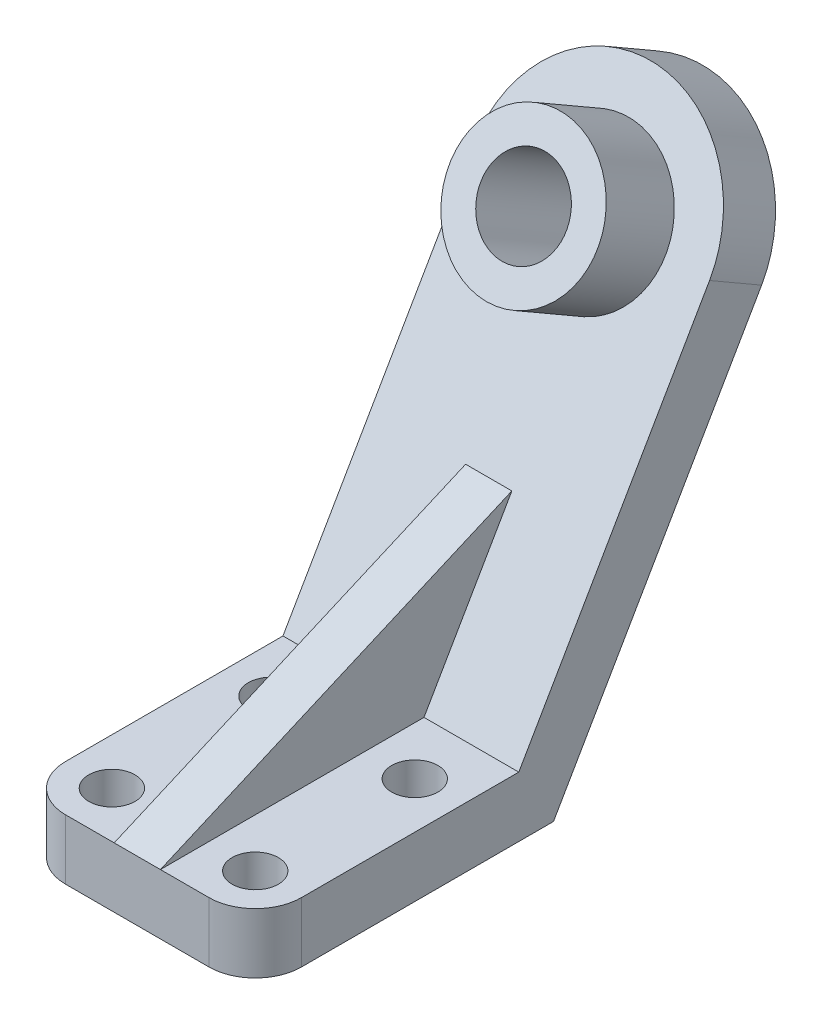
SolidWorks part; units mm, degrees
ref_plane "Front Plane" through (0, 0, 0) normal (0, 0, 1) x (1, 0, 0)
ref_plane "Top Plane" through (0, 0, 0) normal (0, 1, 0) x (1, 0, 0)
ref_plane "Right Plane" through (0, 0, 0) normal (1, 0, 0) x (0, 0, -1)
sketch "Sketch2" plane through (0, 0, 0) normal (1, 0, 0) x (0, 0, -1)
  line L0 (54.3162, 0) -> (129, 0)
  line L1 (0, 0) -> (129, 0)
  line L2 (0, 0) -> (0, 26)
  line L3 (0, 26) -> (113.9889, 26)
  line L5 (113.9889, 26) -> (221.9833, 213.0519)
  line L6 (129, 0) -> (244.5, 200.0519)
  line L9 (244.5, 200.0519) -> (221.9833, 213.0519)
  dimension "D1" = 120
  dimension "D2" = 129
  dimension "D3" = 231
  dimension "D4" = 26
  dimension "D5" = 26
extrude "Boss-Extrude1" add sketch "Sketch2" along normal mid plane 102 contours L6 L9 L5 L3 L2 L1 L0
sketch "Sketch3" plane through (0, -42.8586, -74.2333) normal (0, 0.5, 0.866) x (1, 0, 0)
  line L0 (-51, 79.5111) -> (-51, 295.5) construction
  line L2 (51, 295.5) -> (-51, 295.5) construction
  line L3 (-51, 244.5) -> (-51, 295.5)
  line L4 (-51, 295.5) -> (0, 295.5)
  line L5 (0, 295.5) -> (51, 295.5)
  line L6 (51, 244.5) -> (51, 295.5)
  circle A0 centre (0, 244.5) radius 51
  line M3 (-51, 295.5) -> (-51, 79.5111)
  line M5 (51, 79.5111) -> (51, 295.5)
  line M6 (51, 295.5) -> (-51, 295.5)
  dimension "D1" = 102
extrude "Cut-Extrude1" cut sketch "Sketch3" against normal blind 102 contours A0 M6 M3 | A0 M5 M6
sketch "Sketch4" plane through (0, -42.8586, -74.2333) normal (0, 0.5, 0.866) x (1, 0, 0)
  circle A0 centre (0, 244.5) radius 32
  dimension "D1" = 64
extrude "Boss-Extrude2" add sketch "Sketch4" along normal blind 60 from surface at -26 starting at face at (0, 88.9841, -180.375)
sketch "Sketch5" plane through (0, -25.8586, -44.7885) normal (0, 0.5, 0.866) x (1, 0, 0)
  circle A0 centre (0, 244.5) radius 18.5
  circle A1 centre (0, 244.5) radius 32
  circle A2 centre (0, 244.5) radius 32
  dimension "D2" = 37
  dimension "D1" = 0
extrude "Cut-Extrude2" cut sketch "Sketch5" against normal through all contours A0
sketch "Sketch6" plane through (0, 0, 0) normal (1, 0, 0) x (0, 0, -1)
  line L0 (0, 26) -> (151.9889, 91.8179)
  line L1 (113.9889, 26) -> (196.4833, 168.8846) construction
  line L2 (151.9889, 91.8179) -> (113.9889, 26)
  line L3 (113.9889, 26) -> (0, 26)
  dimension "D1" = 76
extrude "Boss-Extrude3" add sketch "Sketch6" along normal mid plane 20
sketch "Sketch7" plane through (0, 26, 0) normal (0, 1, 0) x (1, 0, 0)
  circle A0 centre (31, 20) radius 10
  circle A1 centre (-31, 20) radius 10
  circle A2 centre (-31, 89) radius 10
  circle A3 centre (31, 89) radius 10
  dimension "D3" = 20
  dimension "D6" = 62
  dimension "D1" = 20
  dimension "D2" = 20
  dimension "D7" = 69
  dimension "D4" = 2
  dimension "D5" = 2
extrude "Cut-Extrude3" cut sketch "Sketch7" against normal through all
fillet "Fillet1" radius 20 2 edges at (-51, 13, 0) (51, 13, 0)
